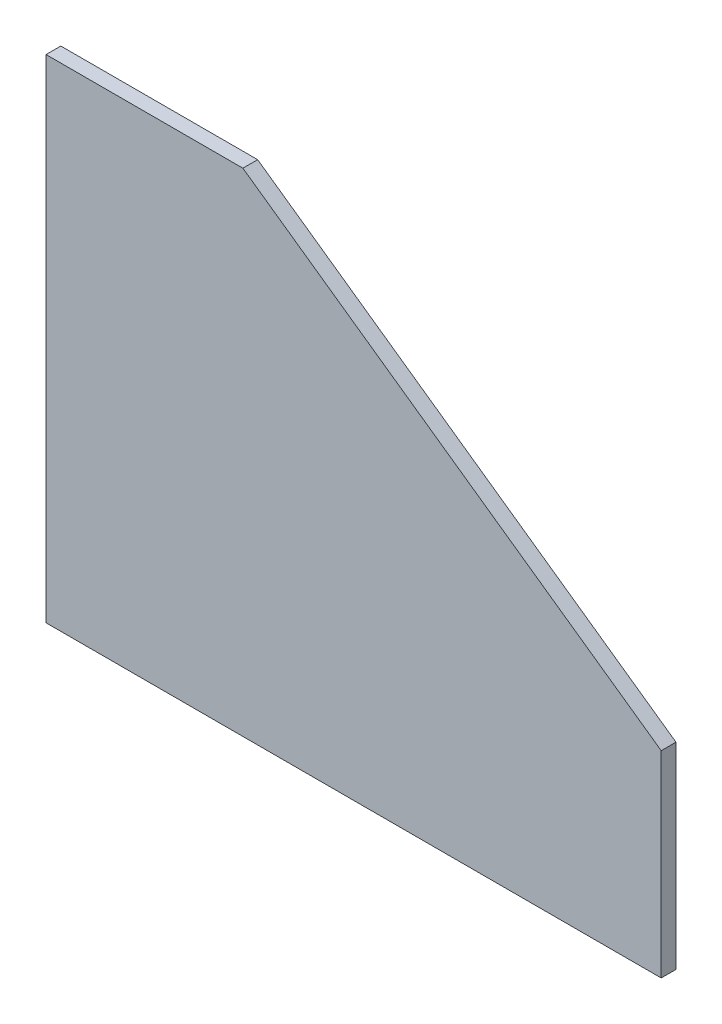
SolidWorks part; units mm, degrees
ref_plane "Alzado" through (0, 0, 0) normal (0, 0, 1) x (1, 0, 0)
ref_plane "Planta" through (0, 0, 0) normal (0, 1, 0) x (1, 0, 0)
ref_plane "Vista lateral" through (0, 0, 0) normal (1, 0, 0) x (0, 0, -1)
sketch "Croquis1" plane through (0, 0, 0) normal (0, 0, 1) x (1, 0, 0)
  line L0 (0, 0) -> (250, 0)
  line L1 (250, 0) -> (250, 80)
  line L2 (250, 80) -> (80, 200)
  line L3 (80, 200) -> (0, 200)
  line L4 (0, 200) -> (0, 0)
  dimension "D1" = 250
  dimension "D2" = 200
  dimension "D3" = 80
  dimension "D4" = 80
extrude "Saliente-Extruir1" add sketch "Croquis1" along normal blind 6
